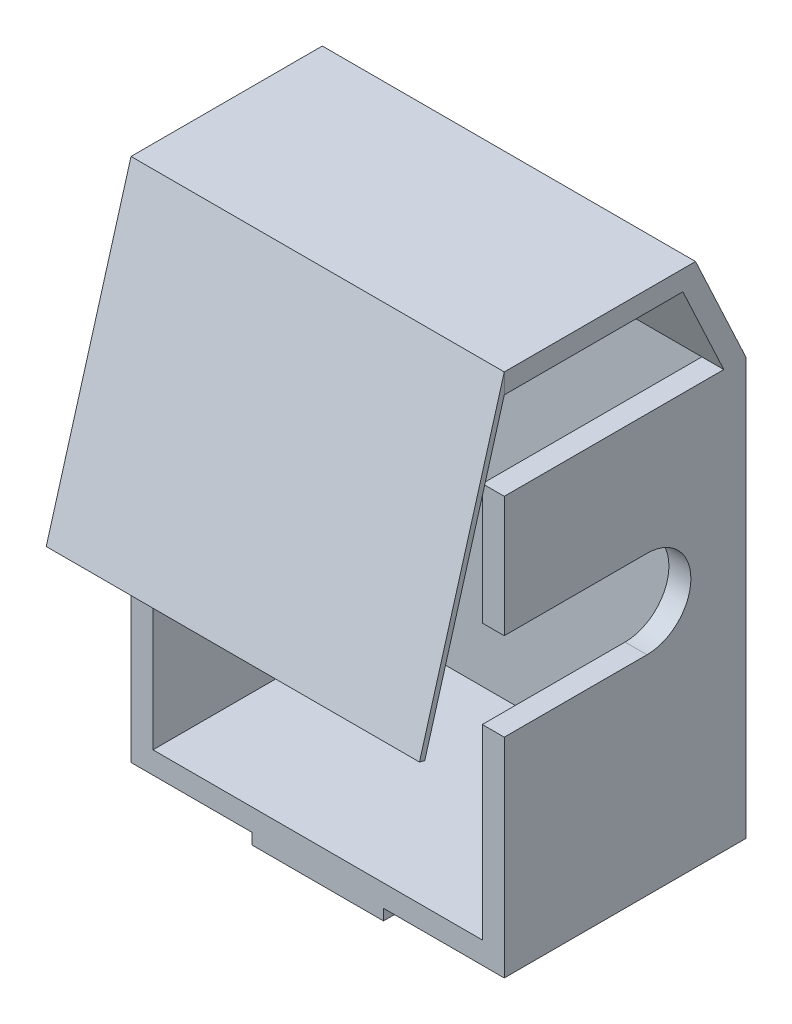
SolidWorks part; units mm, degrees
material "Plain Carbon Steel"
ref_plane "Front Plane" through (0, 0, 0) normal (0, 0, 1) x (1, 0, 0)
ref_plane "Top Plane" through (0, 0, 0) normal (0, 1, 0) x (1, 0, 0)
ref_plane "Right Plane" through (0, 0, 0) normal (1, 0, 0) x (0, 0, -1)
sketch "Sketch1" plane through (0, 0, 0) normal (0, 0, 1) x (1, 0, 0)
  line L0 (0, 0) -> (0, 19.05) construction
  line L1 (-107.95, 19.05) -> (107.95, 19.05)
  line L2 (107.95, 19.05) -> (107.95, 6.35)
  line L3 (107.95, 6.35) -> (38.1, 6.35)
  line L4 (38.1, 6.35) -> (38.1, 0)
  line L5 (38.1, 0) -> (-38.1, 0)
  line L6 (-38.1, 6.35) -> (-38.1, 0)
  line L7 (-107.95, 6.35) -> (-38.1, 6.35)
  line L8 (-107.95, 19.05) -> (-107.95, 6.35)
  dimension "D1" = 76.2
  dimension "D2" = 12.7
  dimension "D3" = 215.9
  dimension "D4" = 6.35
extrude "Boss-Extrude1" add sketch "Sketch1" along normal mid plane 139.7
sketch "Sketch2" plane through (0, 19.05, 0) normal (0, 1, 0) x (1, 0, 0)
  line L4 (107.95, 69.85) -> (-107.95, 69.85)
  line L5 (-107.95, 69.85) -> (-107.95, -69.85)
  line L6 (-107.95, -69.85) -> (107.95, -69.85)
  line L7 (107.95, -69.85) -> (107.95, 69.85)
  line L8 (107.95, 69.85) -> (-107.95, 69.85)
  line L9 (-107.95, 69.85) -> (-107.95, -69.85)
  line L11 (107.95, -69.85) -> (107.95, 69.85)
  line L12 (-107.95, -69.85) -> (-95.25, -69.85)
  line L13 (107.95, -69.85) -> (95.25, -69.85)
  line L14 (107.95, -69.85) -> (-107.95, -69.85) construction
  line L16 (95.25, 57.15) -> (-95.25, 57.15)
  line L17 (-95.25, 57.15) -> (-95.25, -57.15)
  line L18 (-95.25, -57.15) -> (95.25, -57.15)
  line L19 (95.25, -57.15) -> (95.25, 57.15)
  line L20 (95.25, 57.15) -> (-95.25, 57.15)
  line L21 (-95.25, 57.15) -> (-95.25, -69.85)
  line L23 (95.25, -69.85) -> (95.25, 57.15)
  dimension "D1" = 0
  dimension "D2" = 12.7
extrude "Boss-Extrude2" add sketch "Sketch2" along normal blind 228.6
sketch "Sketch3" plane through (107.95, 0, 0) normal (1, 0, 0) x (0, 0, -1)
  line L0 (-69.85, 247.65) -> (69.85, 247.65)
  line L1 (57.15, 247.65) -> (69.85, 247.65)
  line L2 (57.15, 247.65) -> (33.4616, 298.45)
  line L3 (33.4616, 298.45) -> (-69.85, 298.45)
  line L4 (69.85, 247.65) -> (40.7943, 309.9601)
  line L5 (40.7943, 309.9601) -> (-69.85, 309.9601)
  line L6 (67.5817, 252.5144) -> (40.7943, 309.9601) construction
  line L7 (-69.85, 247.65) -> (69.85, 247.65) construction
  line L8 (-69.85, 309.9601) -> (-69.85, 298.45)
  line L9 (-69.85, 6.35) -> (-69.85, 247.65) construction
  dimension "D1" = 65
  dimension "D2" = 50.8
extrude "Boss-Extrude3" add sketch "Sketch3" against normal through all
sketch "Sketch4" plane through (107.95, 0, 0) normal (1, 0, 0) x (0, 0, -1)
  line L0 (-69.85, 298.45) -> (-69.85, 309.9601)
  line L1 (-69.85, 309.9601) -> (-118.8951, 139.0583)
  line L2 (-118.8951, 139.0583) -> (-115.8433, 138.1825)
  line L3 (-115.8433, 138.1825) -> (-69.85, 298.45)
  dimension "D1" = 3.175
  dimension "D2" = 177.8
extrude "Boss-Extrude4" add sketch "Sketch4" against normal up to vertex (215.9 mm away) separate body
sketch "Sketch5" plane through (107.95, 0, 0) normal (1, 0, 0) x (0, 0, -1)
  line L0 (12.7, 177.8) -> (-69.85, 177.8)
  line L1 (-69.85, 6.35) -> (-69.85, 247.65) construction
  line L2 (12.7, 127) -> (-69.85, 127)
  line L3 (-69.85, 127) -> (-69.85, 177.8)
  line L5 (-69.85, 6.35) -> (69.85, 6.35) construction
  arc A2 (12.7, 127) -> (12.7, 177.8) centre (12.7, 152.4) ccw
  dimension "D1" = 50.8
  dimension "D2" = 146.05
  dimension "D3" = 82.55
extrude "Cut-Extrude1" cut sketch "Sketch5" against normal up to next (12.7 mm away)
